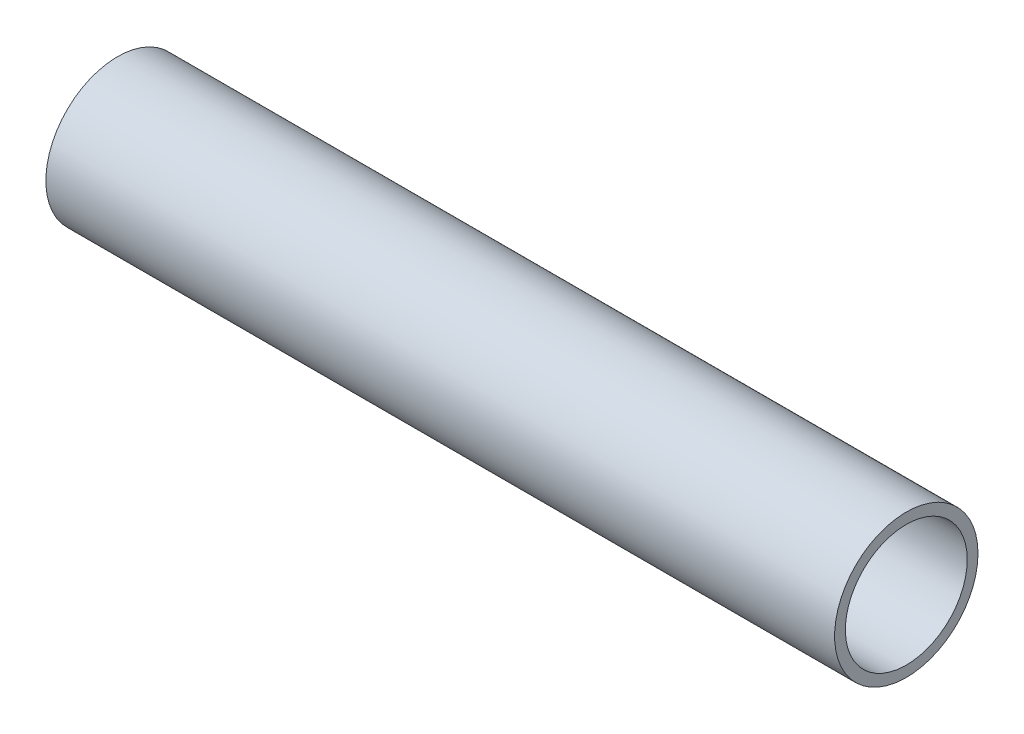
SolidWorks part; units mm, degrees
ref_plane "前视基准面" through (0, 0, 0) normal (0, 0, 1) x (1, 0, 0)
ref_plane "上视基准面" through (0, 0, 0) normal (0, 1, 0) x (1, 0, 0)
ref_plane "右视基准面" through (0, 0, 0) normal (1, 0, 0) x (0, 0, -1)
sketch "草图1" plane through (0, 0, 0) normal (1, 0, 0) x (0, 0, -1)
  circle A0 centre (0, 0) radius 10
  circle A1 centre (0, 0) radius 8.5
  dimension "D1" = 20
  dimension "D2" = 17
extrude "凸台-拉伸1" add sketch "草图1" along normal blind 110
